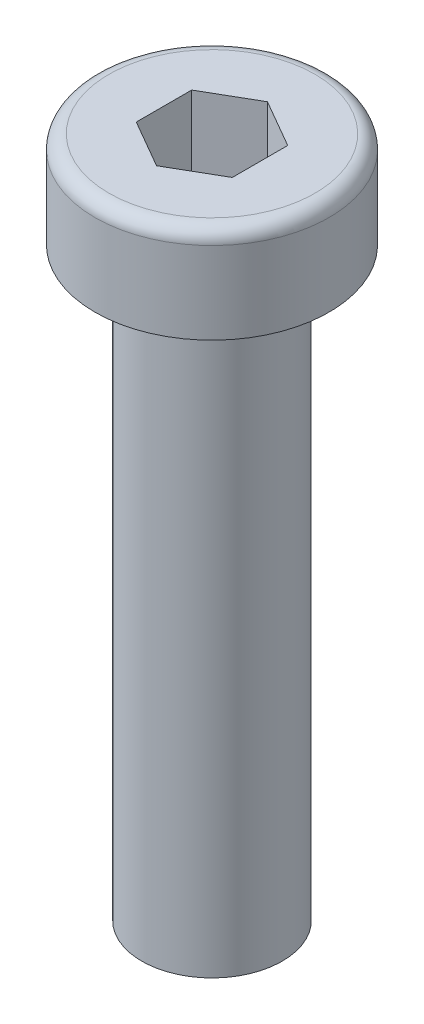
SolidWorks part; units mm, degrees
ref_plane "Front Plane" through (0, 0, 0) normal (0, 0, 1) x (1, 0, 0)
ref_plane "Top Plane" through (0, 0, 0) normal (0, 1, 0) x (1, 0, 0)
ref_plane "Right Plane" through (0, 0, 0) normal (1, 0, 0) x (0, 0, -1)
sketch "Sketch1" plane through (0, 0, 0) normal (0, 1, 0) x (1, 0, 0)
  circle A0 centre (0, 0) radius 5
  dimension "D1" = 10
extrude "Boss-Extrude1" add sketch "Sketch1" along normal blind 4.1
fillet "Fillet1" radius 0.6 1 edges at (0, 4.1, 5)
sketch "Sketch2" plane through (0, 4.1, 0) normal (0, 1, 0) x (1, 0, 0)
  line L1 (0, -2.3671) -> (2.05, -1.1836)
  line L2 (2.05, -1.1836) -> (2.05, 1.1836)
  line L3 (2.05, 1.1836) -> (0, 2.3671)
  line L4 (0, 2.3671) -> (-2.05, 1.1836)
  line L5 (-2.05, 1.1836) -> (-2.05, -1.1836)
  line L6 (-2.05, -1.1836) -> (0, -2.3671)
  circle A0 centre (0, 0) radius 2.05 construction
  dimension "D1" = 4.1
extrude "Cut-Extrude1" cut sketch "Sketch2" against normal blind 3.6
sketch "Sketch3" plane through (0, 0, 0) normal (0, -1, 0) x (1, 0, 0)
  circle A0 centre (0, 0) radius 3
  dimension "D1" = 6
extrude "Boss-Extrude2" add sketch "Sketch3" along normal blind 25
